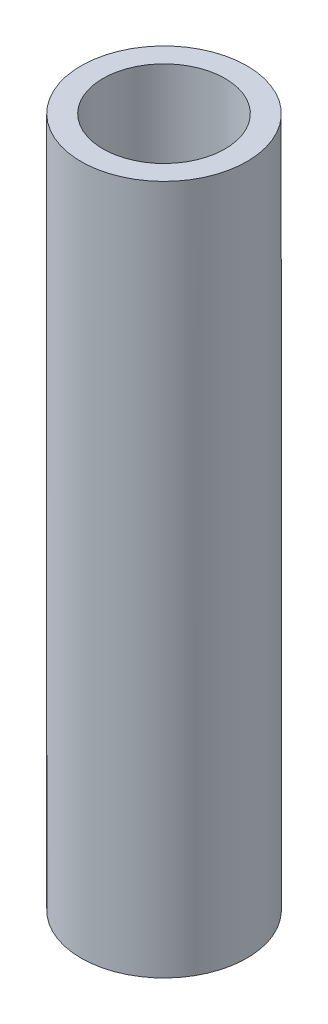
SolidWorks part; units mm, degrees
ref_plane "Top Plane" through (0, 0, 0) normal (0, 0, 1) x (1, 0, 0)
ref_plane "Front Plane" through (0, 0, 0) normal (0, 1, 0) x (1, 0, 0)
ref_plane "Right Plane" through (0, 0, 0) normal (1, 0, 0) x (0, 0, -1)
sketch "Sketch1" plane through (0, 0, 0) normal (0, 1, 0) x (1, 0, 0)
  circle A0 centre (0, 0) radius 4.0894
  circle A1 centre (0, 0) radius 5.5562
  dimension "D1" = 8.1788
  dimension "D2" = 11.1125
extrude "Boss-Extrude1" add sketch "Sketch1" along normal up to surface (46.2 mm away)
